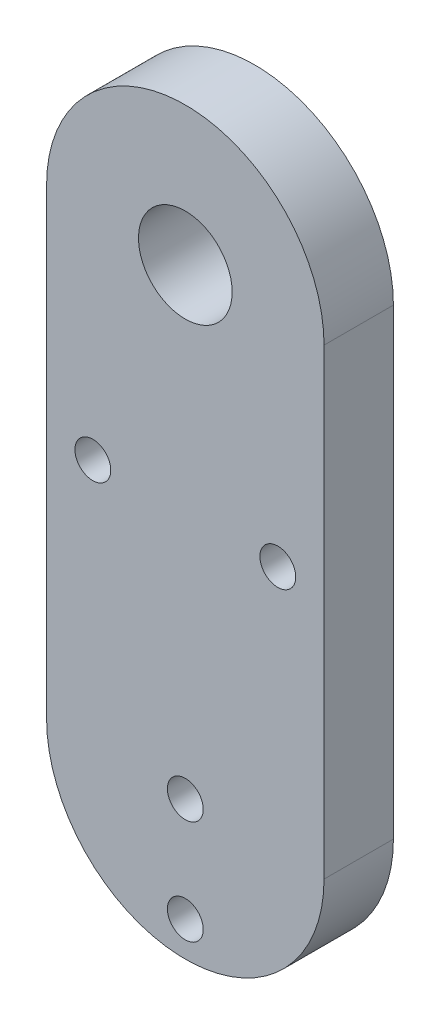
SolidWorks part; units mm, degrees
ref_plane "Płaszczyzna przednia" through (0, 0, 0) normal (0, 0, 1) x (1, 0, 0)
ref_plane "Płaszczyzna górna" through (0, 0, 0) normal (0, 1, 0) x (1, 0, 0)
ref_plane "Płaszczyzna prawa" through (0, 0, 0) normal (1, 0, 0) x (0, 0, -1)
sketch "Szkic1" plane through (0, 0, 0) normal (0, 0, 1) x (1, 0, 0)
  line L4 (-200.1811, 116.9248) -> (-200.1811, 76.9248)
  line L5 (-176.1811, 76.9248) -> (-176.1811, 116.9248)
  arc A4 (-176.1811, 116.9248) -> (-200.1811, 116.9248) centre (-188.1811, 116.9248) ccw
  arc A5 (-200.1811, 76.9248) -> (-176.1811, 76.9248) centre (-188.1811, 76.9248) ccw
  dimension "D1" = 40
  dimension "D3" = 12
  dimension "D4" = 12
  dimension "D2" = 24
extrude "Dodanie-wyciągnięcie1" add sketch "Szkic1" along normal blind 6
sketch "Szkic2" plane through (0, 0, 6) normal (0, 0, 1) x (1, 0, 0)
  circle A1 centre (-196.1811, 98.3248) radius 1.55 construction
  circle A2 centre (-180.1811, 98.3248) radius 1.55 construction
  circle A3 centre (-188.1811, 67.9248) radius 1.55 construction
  circle A4 centre (-196.1811, 98.3248) radius 1.55
  circle A5 centre (-180.1811, 98.3248) radius 1.55
  circle A6 centre (-188.1811, 67.9248) radius 1.55
extrude "Wytnij-wyciągnięcie1" cut sketch "Szkic2" against normal blind 6
sketch "Szkic5" plane through (0, 0, 6) normal (0, 0, 1) x (1, 0, 0)
  circle A0 centre (-188.1811, 116.9248) radius 4.05
  arc A1 (-176.1811, 116.9248) -> (-200.1811, 116.9248) centre (-188.1811, 116.9248) ccw construction
  dimension "D1" = 8.1
  dimension "D2" = 0
extrude "Wytnij-wyciągnięcie3" cut sketch "Szkic5" against normal blind 6
sketch "Szkic7" plane through (0, 0, 6) normal (0, 0, 1) x (1, 0, 0)
  circle A0 centre (-188.1811, 76.9248) radius 1.55
  arc A1 (-200.1811, 76.9248) -> (-176.1811, 76.9248) centre (-188.1811, 76.9248) ccw construction
  dimension "D1" = 0
  dimension "D2" = 3.1
extrude "Wytnij-wyciągnięcie5" cut sketch "Szkic7" against normal blind 10
equation "\"tolerancja_wpusy\"=0.2"
equation "\"dlugosc_wpustu_duzy\"=20"
equation "\"srednica_otworu_M3\"=3.1"
equation "\"szerokosc_nogi_T\"=3.1"
equation "\"dlugosc_T_30\"=11"
equation "\"grubosc_na_nakretke_kwadrat\"=2"
equation "\"szerokosc_na_nakretke_kwadrat\"=5.85"
equation "\"wyokosc_nadstawki_T\"=0.5"
equation "\"dlugosc_T_20_6\"=14"
